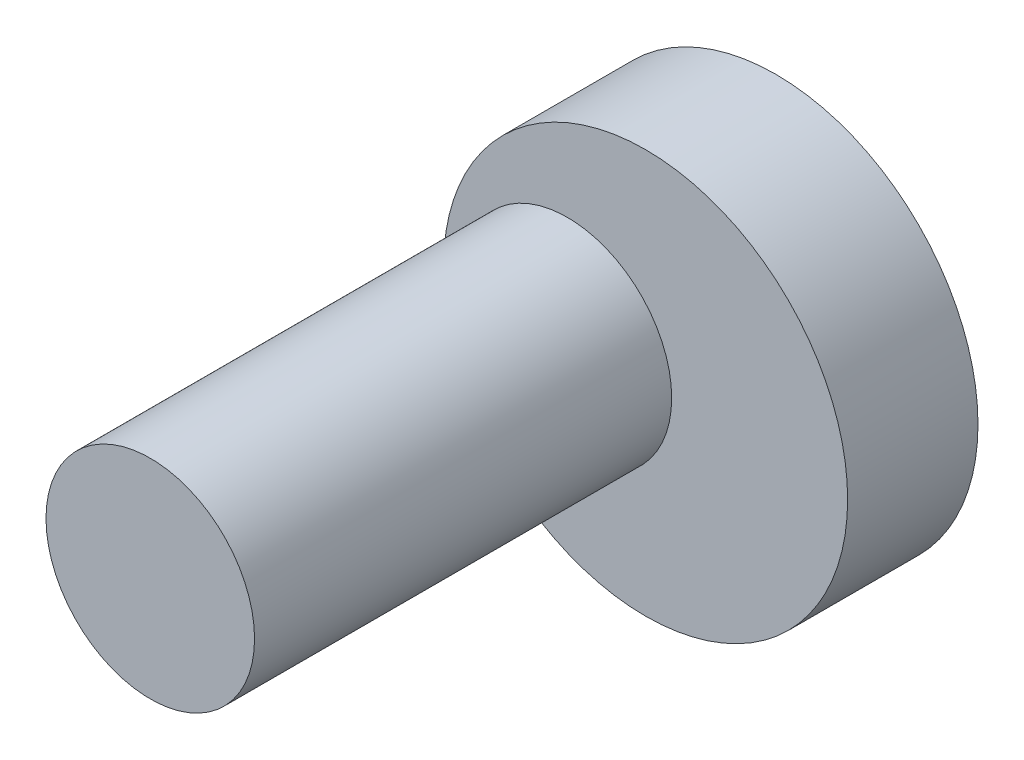
SolidWorks part; units mm, degrees
ref_plane "前视基准面" through (0, 0, 0) normal (0, 0, 1) x (1, 0, 0)
ref_plane "上视基准面" through (0, 0, 0) normal (0, 1, 0) x (1, 0, 0)
ref_plane "右视基准面" through (0, 0, 0) normal (1, 0, 0) x (0, 0, -1)
other "Configuration Table"
sketch "草图1" plane through (0, 0, 0) normal (0, 0, 1) x (1, 0, 0)
  circle A0 centre (0, 0) radius 15.5
  dimension "D1" = 31
extrude "凸台-拉伸1" add sketch "草图1" along normal blind 10
sketch "草图2" plane through (0, 0, 10) normal (0, 0, 1) x (1, 0, 0)
  circle A0 centre (-6, 0) radius 8
  point P2 (0, 0)
  dimension "D1" = 16
  dimension "D2" = 6
extrude "凸台-拉伸2" add sketch "草图2" along normal blind 32
